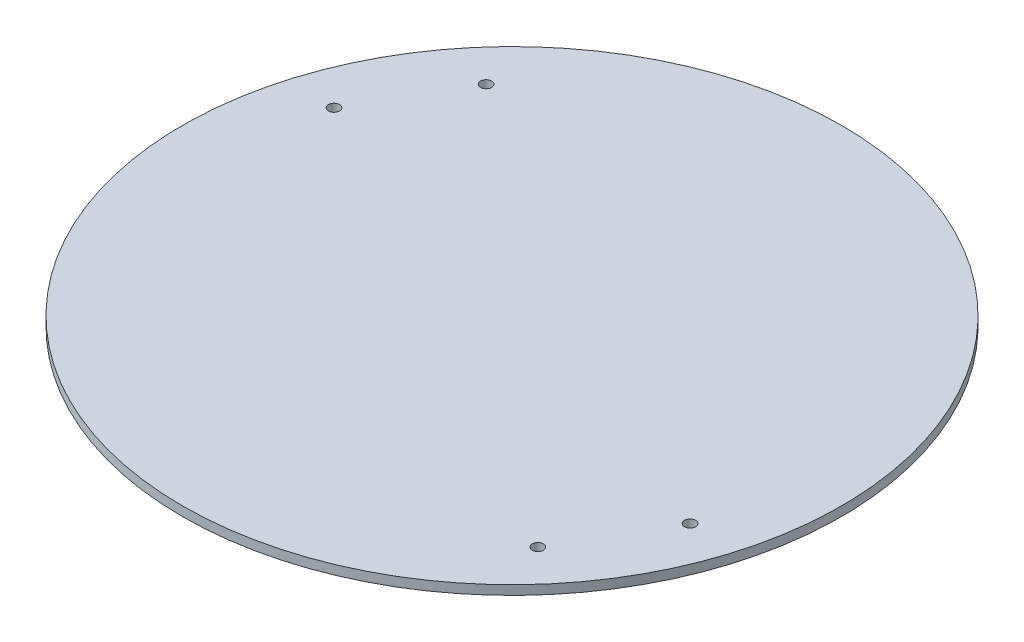
SolidWorks part; units mm, degrees
ref_plane "前视基准面" through (0, 0, 0) normal (0, 0, 1) x (1, 0, 0)
ref_plane "上视基准面" through (0, 0, 0) normal (0, 1, 0) x (1, 0, 0)
ref_plane "右视基准面" through (0, 0, 0) normal (1, 0, 0) x (0, 0, -1)
other "Configuration Table"
sketch "草图1" plane through (0, 0, 0) normal (0, 1, 0) x (1, 0, 0)
  circle A1 centre (20.4352, -16.4023) radius 3 construction
  circle A2 centre (20.4352, -16.4023) radius 3
  circle A3 centre (-9.5648, -68.3639) radius 3 construction
  circle A4 centre (-9.5648, -68.3639) radius 3
  circle A5 centre (250.2428, -218.3639) radius 3 construction
  circle A6 centre (250.2428, -218.3639) radius 3
  circle A7 centre (135.339, -117.3831) radius 152.9706 construction
  circle A8 centre (280.2428, -166.4023) radius 3
  circle A9 centre (280.2428, -166.4023) radius 3
  circle A11 centre (135.339, -117.3831) radius 177.5
  dimension "D2" = 355
  dimension "D1" = 0
extrude "凸台-拉伸1" add sketch "草图1" along normal blind 5
